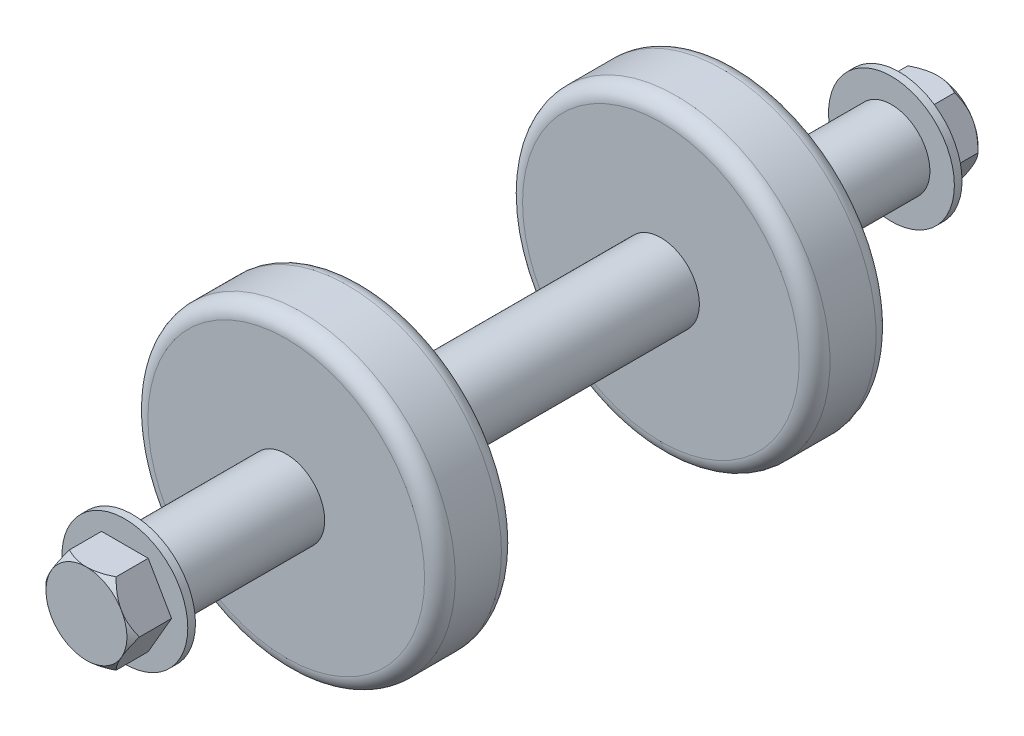
SolidWorks part; units mm, degrees
ref_plane "Front Plane" through (0, 0, 0) normal (0, 0, 1) x (1, 0, 0)
ref_plane "Top Plane" through (0, 0, 0) normal (0, 1, 0) x (1, 0, 0)
ref_plane "Right Plane" through (0, 0, 0) normal (1, 0, 0) x (0, 0, -1)
sketch "Sketch1" plane through (0, 0, 0) normal (0, 0, 1) x (1, 0, 0)
  circle A0 centre (0, 0) radius 25
  dimension "D1" = 50
extrude "Boss-Extrude1" add sketch "Sketch1" along normal mid plane 493.75
ref_plane "Plane1" through (0, 0, 146.875) normal (0, 0, 1) x (1, 0, 0)
sketch "Sketch2" plane through (0, 0, 146.875) normal (0, 0, 1) x (1, 0, 0)
  circle A0 centre (0, 0) radius 100
  dimension "D1" = 200
extrude "Boss-Extrude2" add sketch "Sketch2" against normal blind 50
mirror "Mirror1" about plane through (0, 0, 0) normal (0, 0, 1) of "Boss-Extrude2"
fillet "Fillet1" radius 10 4 edges at (100, 0, -146.875) (100, 0, -96.875) (100, 0, 146.875) (100, 0, 96.875)
sketch "Sketch3" plane through (0, 0, 246.875) normal (0, 0, 1) x (1, 0, 0)
  circle A0 centre (0, 0) radius 40.935
  dimension "D1" = 81.87
extrude "Boss-Extrude3" add sketch "Sketch3" along normal blind 5
sketch "Sketch4" plane through (0, 0, 251.875) normal (0, 0, 1) x (1, 0, 0)
  line L1 (-30.3802, 0) -> (-15.1901, -26.31)
  line L2 (-15.1901, -26.31) -> (15.1901, -26.31)
  line L3 (15.1901, -26.31) -> (30.3802, 0)
  line L4 (30.3802, 0) -> (15.1901, 26.31)
  line L5 (15.1901, 26.31) -> (-15.1901, 26.31)
  line L6 (-15.1901, 26.31) -> (-30.3802, 0)
  circle A0 centre (0, 0) radius 26.31 construction
  dimension "D1" = 52.62
extrude "Boss-Extrude4" add sketch "Sketch4" along normal blind 25
sketch "Sketch5" plane through (0, 0, 276.875) normal (0, 0, 1) x (1, 0, 0)
  line L0 (-15.1901, -26.31) -> (15.1901, -26.31) construction
  circle A0 centre (0, 0) radius 26.31
  circle A1 centre (0, 0) radius 34.8089
extrude "Cut-Extrude1" cut sketch "Sketch5" against normal blind 25 draft 45
mirror "Mirror2" about plane through (0, 0, 0) normal (0, 0, 1) of "Boss-Extrude3", "Boss-Extrude4", "Cut-Extrude1"
